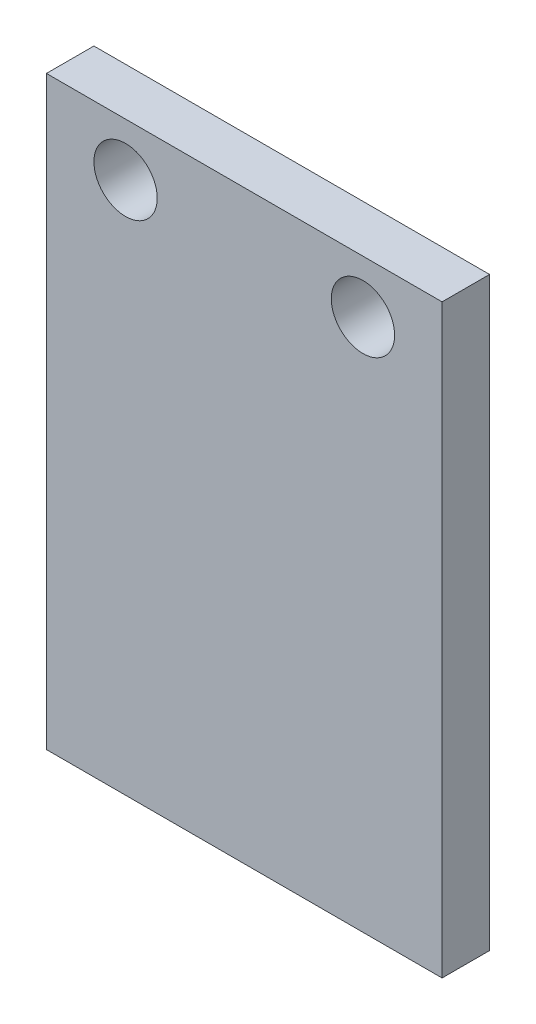
SolidWorks part; units mm, degrees
material "Balsa"
ref_plane "Alzado" through (0, 0, 0) normal (0, 0, 1) x (1, 0, 0)
ref_plane "Planta" through (0, 0, 0) normal (0, 1, 0) x (1, 0, 0)
ref_plane "Vista lateral" through (0, 0, 0) normal (1, 0, 0) x (0, 0, -1)
sketch "Croquis1" plane through (0, 0, 0) normal (0, 0, 1) x (1, 0, 0)
  line L0 (-7.5, 15.17) -> (7.5, 15.17) construction
  line L1 (-12.5, -18.5) -> (12.5, -18.5)
  line L2 (-12.5, -18.5) -> (-12.5, 18.5)
  line L3 (-12.5, 18.5) -> (12.5, 18.5)
  line L4 (12.5, -18.5) -> (12.5, 18.5)
  line L5 (-12.5, -18.5) -> (12.5, 18.5) construction
  line L6 (-12.5, 18.5) -> (12.5, -18.5) construction
  line L7 (0, 0) -> (0, 15.17) construction
  line L8 (-18.0411, -15.5) -> (25.8031, -15.5) construction
  circle A0 centre (-7.5, 15.17) radius 2
  circle A1 centre (7.5, 15.17) radius 2
  point P0 (0, 0)
  dimension "D6" = 4
  dimension "D7" = 4
  dimension "D1" = 25
  dimension "D2" = 37
  dimension "D3" = 15
  dimension "D4" = 3
  dimension "D5" = 30.67
extrude "Saliente-Extruir1" add sketch "Croquis1" along normal mid plane 3
